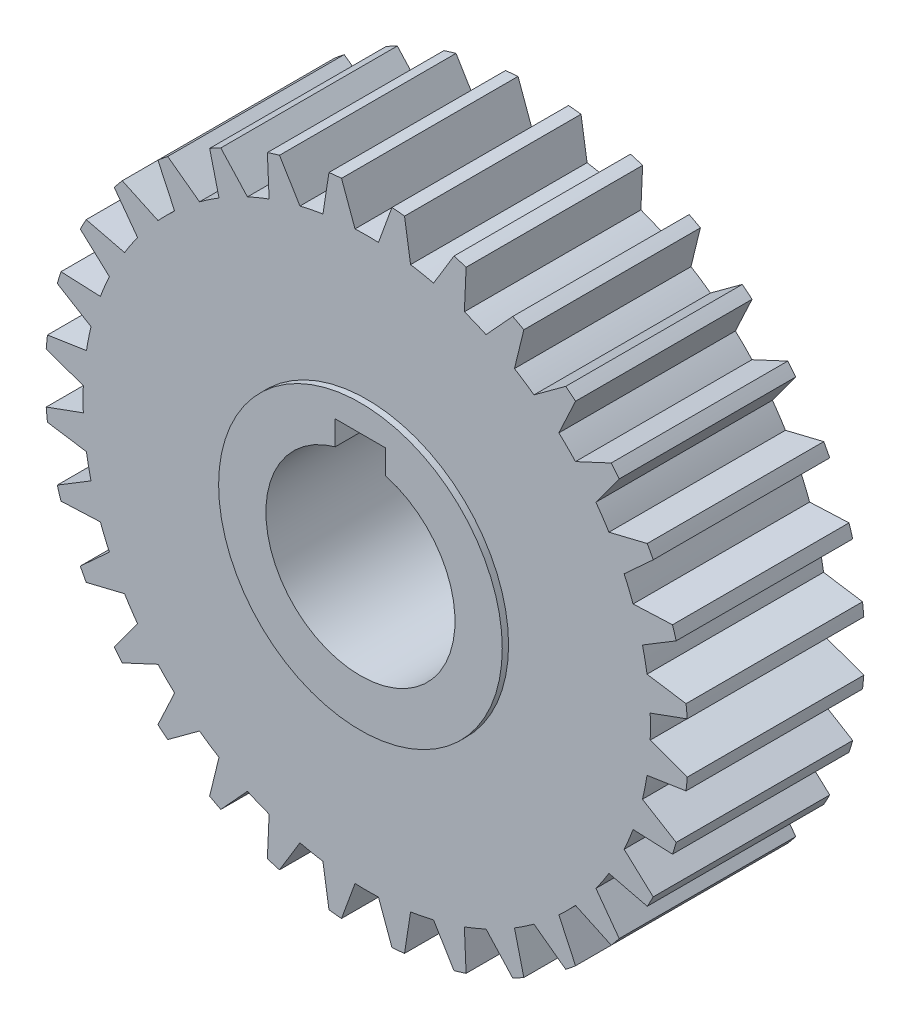
SolidWorks part; units mm, degrees
ref_plane "前视基准面" through (0, 0, 0) normal (0, 0, 1) x (1, 0, 0)
ref_plane "上视基准面" through (0, 0, 0) normal (0, 1, 0) x (1, 0, 0)
ref_plane "右视基准面" through (0, 0, 0) normal (1, 0, 0) x (0, 0, -1)
sketch "草图1" plane through (0, 0, 0) normal (0, 0, 1) x (1, 0, 0)
  circle A0 centre (0, 0) radius 51
  dimension "D1" = 102
extrude "凸台-拉伸1" add sketch "草图1" along normal blind 28
sketch "草图2" plane through (0, 0, 0) normal (0, 0, -1) x (-1, 0, 0)
  circle A0 centre (0, 0) radius 22.5
  dimension "D1" = 45
extrude "凸台-拉伸2" add sketch "草图2" along normal blind 1
sketch "草图3" plane through (0, 0, 28) normal (0, 0, 1) x (1, 0, 0)
  circle A0 centre (0, 0) radius 22.5
  dimension "D1" = 45
extrude "凸台-拉伸3" add sketch "草图3" along normal blind 1
sketch "草图4" plane through (0, 0, -1) normal (0, 0, -1) x (-1, 0, 0)
  line L0 (-62.3961, 18.3) -> (65.0123, 18.3) construction
  line L1 (0, 32.4408) -> (0, 4.1859) construction
  line L2 (-4, 18.3) -> (-4, 14.4568)
  line L3 (-4, 18.3) -> (4, 18.3)
  line L4 (4, 18.3) -> (4, 14.4568)
  arc A0 (-4, 14.4568) -> (4, 14.4568) centre (0, 0) ccw
  dimension "D1" = 30
  dimension "D2" = 18.3
  dimension "D3" = 8
  dimension "D4" = 4
extrude "切除-拉伸1" cut sketch "草图4" against normal up to next
sketch "草图5" plane through (0, 0, 0) normal (0, 0, -1) x (-1, 0, 0)
  line L0 (0, 53.6319) -> (0, -58.341) construction
  line L1 (-4, 57.0505) -> (-4, 40.5054) construction
  line L2 (4, 57.0505) -> (4, 42.1275) construction
  line L3 (-4, 50.8429) -> (-1.8594, 44.9616)
  line L4 (4, 50.8429) -> (1.8594, 44.9616)
  circle A0 centre (0, 0) radius 48 construction
  circle A1 centre (0, 0) radius 51 construction
  arc A2 (4, 50.8429) -> (-4, 50.8429) centre (0, 0) ccw
  arc A4 (1.8594, 44.9616) -> (-1.8594, 44.9616) centre (0, 0) ccw
  point P17 (45, 0)
  dimension "D1" = 96
  dimension "D4" = 45
  dimension "D2" = 4
  dimension "D3" = 4
  dimension "D5" = 20
  dimension "D6" = 20
extrude "切除-拉伸2" cut sketch "草图5" against normal up to next
pattern_circular "阵列(圆周)1" count 32 over 360 about axis through (0, 0, 0) along (0, 0, 1) of "切除-拉伸2"
